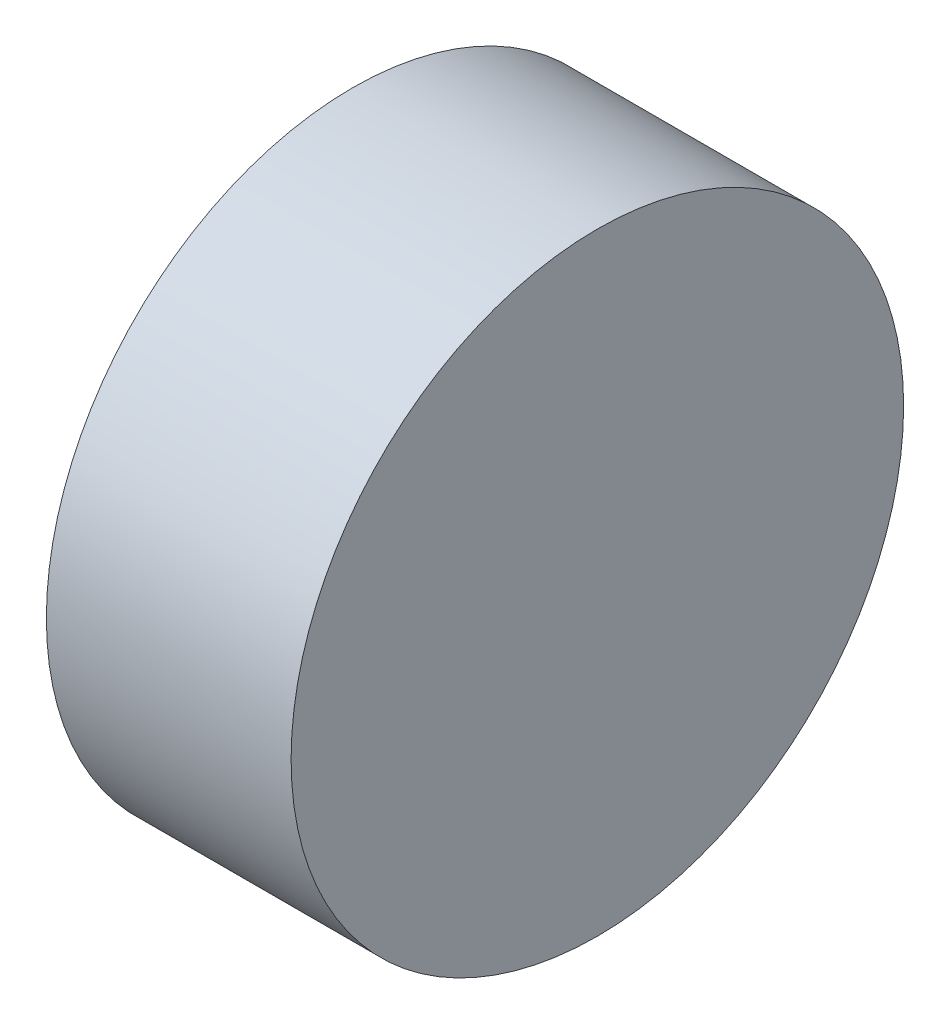
SolidWorks part; units mm, degrees
ref_plane "Front Plane" through (0, 0, 0) normal (0, 0, 1) x (1, 0, 0)
ref_plane "Top Plane" through (0, 0, 0) normal (0, 1, 0) x (1, 0, 0)
ref_plane "Right Plane" through (0, 0, 0) normal (1, 0, 0) x (0, 0, -1)
sketch "Sketch2" plane through (0, 0, 0) normal (1, 0, 0) x (0, 0, -1)
  circle A0 centre (0, 0) radius 21.4
  dimension "D1" = 42.8
extrude "Boss-Extrude1" add sketch "Sketch2" along normal blind 17.1
